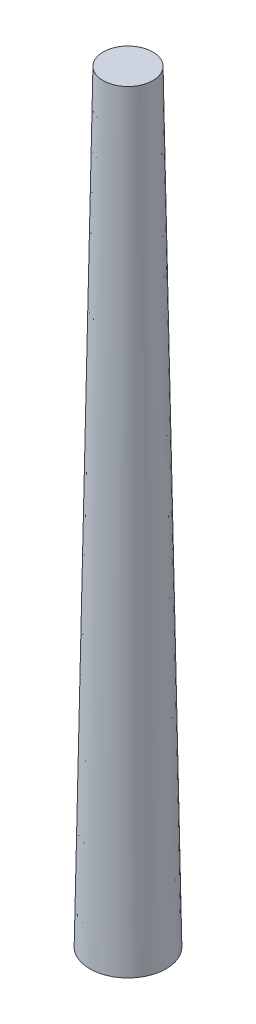
SolidWorks part; units mm, degrees
material "ABS PC"
ref_plane "Front Plane" through (0, 0, 0) normal (0, 0, 1) x (1, 0, 0)
ref_plane "Top Plane" through (0, 0, 0) normal (0, 1, 0) x (1, 0, 0)
ref_plane "Right Plane" through (0, 0, 0) normal (1, 0, 0) x (0, 0, -1)
sketch "Sketch1" plane through (0, 0, 0) normal (0, 1, 0) x (1, 0, 0)
  circle A0 centre (0, 0) radius 5
  dimension "D1" = 10
extrude "Boss-Extrude1" add sketch "Sketch1" along normal blind 100 draft 1
